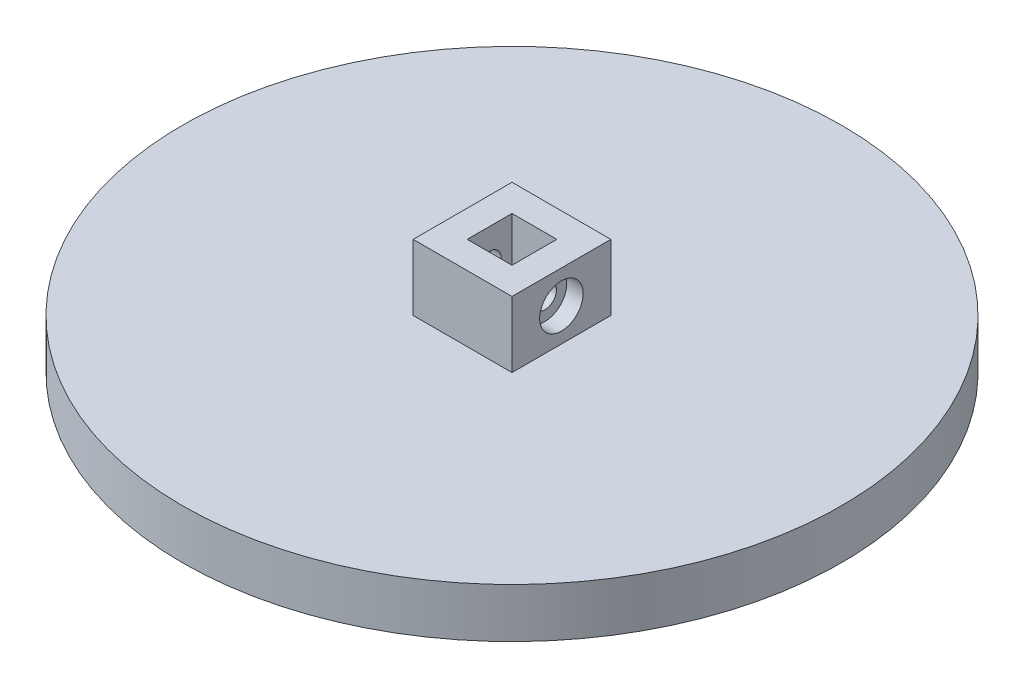
SolidWorks part; units mm, degrees
ref_plane "Front Plane" through (0, 0, 0) normal (0, 0, 1) x (1, 0, 0)
ref_plane "Top Plane" through (0, 0, 0) normal (0, 1, 0) x (1, 0, 0)
ref_plane "Right Plane" through (0, 0, 0) normal (1, 0, 0) x (0, 0, -1)
sketch "Sketch1" plane through (0, 0, 0) normal (0, 1, 0) x (1, 0, 0)
  circle A0 centre (0, 0) radius 50
  point P4 (0, 0)
extrude "Boss-Extrude1" add sketch "Sketch1" along normal blind 7.5
sketch "Sketch2" plane through (0, 7.5, 0) normal (0, 1, 0) x (1, 0, 0)
  line L7 (-7.5, -7.5) -> (7.5, -7.5)
  line L8 (-7.5, -7.5) -> (-7.5, 7.5)
  line L9 (-7.5, 7.5) -> (7.5, 7.5)
  line L10 (7.5, -7.5) -> (7.5, 7.5)
  point P1 (0, 0)
  point P6 (0, 0)
  dimension "D3" = 15
extrude "Boss-Extrude2" add sketch "Sketch2" along normal blind 10
sketch "Sketch3" plane through (7.5, 0, 0) normal (1, 0, 0) x (0, 0, -1)
  line L0 (-7.5, 17.5) -> (7.5, 17.5) construction
  circle A0 centre (0, 12.5) radius 1.75
  dimension "D1" = 5
extrude "Cut-Extrude1" cut sketch "Sketch3" against normal up to surface (15 mm away) up to face at (-7.5, 12.5, 0)
sketch "Sketch4" plane through (7.5, 0, 0) normal (1, 0, 0) x (0, 0, -1)
  circle A0 centre (0, 12.5) radius 3.3
extrude "Cut-Extrude2" cut sketch "Sketch4" against normal blind 2.5
sketch "Sketch5" plane through (-7.5, 0, 0) normal (-1, 0, 0) x (0, 0, 1)
  line L1 (-3.35, 12.5) -> (-1.675, 9.5988)
  line L2 (-1.675, 9.5988) -> (1.675, 9.5988)
  line L3 (1.675, 9.5988) -> (3.35, 12.5)
  line L4 (3.35, 12.5) -> (1.675, 15.4012)
  line L5 (1.675, 15.4012) -> (-1.675, 15.4012)
  line L6 (-1.675, 15.4012) -> (-3.35, 12.5)
  circle A1 centre (0, 12.5) radius 3.35 construction
extrude "Cut-Extrude3" cut sketch "Sketch5" against normal blind 2.5
sketch "Sketch6" plane through (0, 17.5, 0) normal (0, 1, 0) x (1, 0, 0)
  line L1 (-3.4, -3.4) -> (3.4, -3.4)
  line L2 (-3.4, -3.4) -> (-3.4, 3.4)
  line L3 (-3.4, 3.4) -> (3.4, 3.4)
  line L4 (3.4, -3.4) -> (3.4, 3.4)
  line L5 (-3.4, -3.4) -> (3.4, 3.4) construction
  line L6 (-3.4, 3.4) -> (3.4, -3.4) construction
  point P0 (0, 0)
  dimension "D1" = 6.8
  dimension "D2" = 6.8
extrude "Cut-Extrude4" cut sketch "Sketch6" against normal up to surface (17.5 mm away) up to face at (0, 0, 50)
